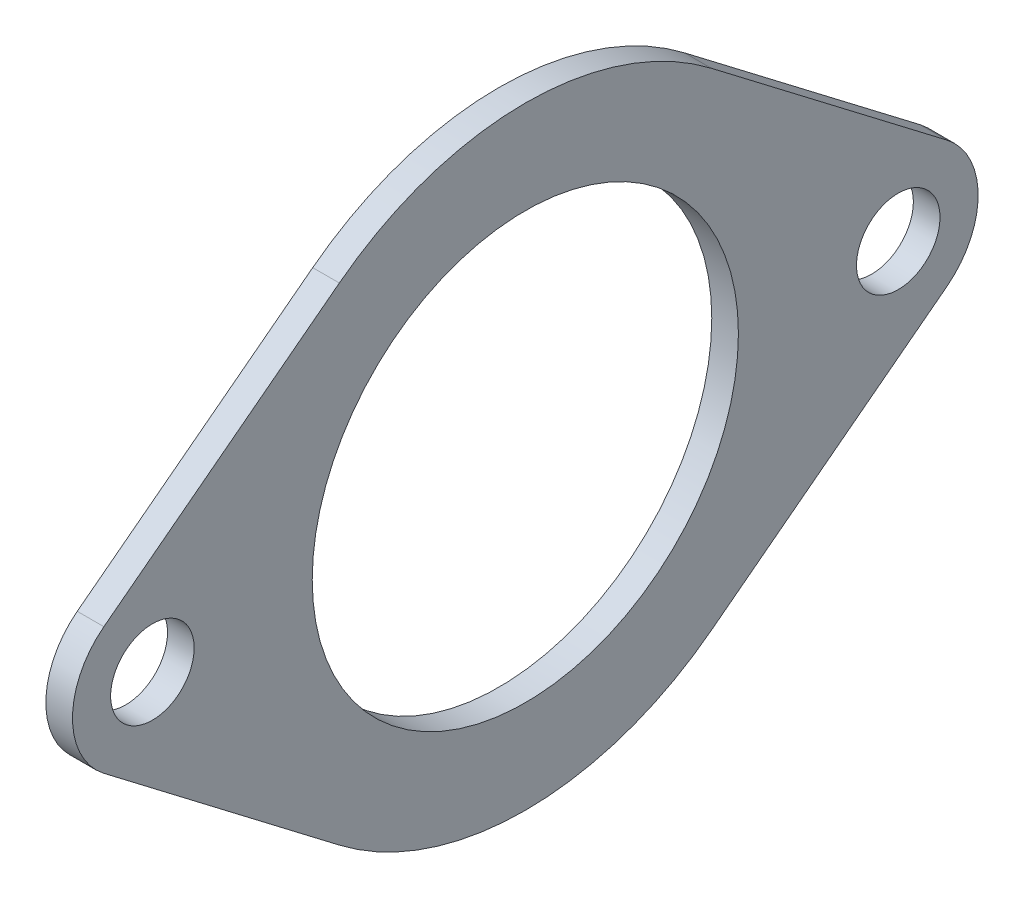
SolidWorks part; units mm, degrees
material "6061-T6 (SS)"
ref_plane "Front Plane" through (0, 0, 0) normal (0, 0, 1) x (1, 0, 0)
ref_plane "Top Plane" through (0, 0, 0) normal (0, 1, 0) x (1, 0, 0)
ref_plane "Right Plane" through (0, 0, 0) normal (1, 0, 0) x (0, 0, -1)
sketch "Sketch1" plane through (0, 0, 0) normal (1, 0, 0) x (0, 0, -1)
  line L0 (22.225, 0) -> (-22.225, 0) construction
  line L1 (-25.1165, -3.7842) -> (-11.0842, -14.5063)
  line L3 (-25.1165, 3.7842) -> (-11.0842, 14.5063)
  line L4 (25.1165, 3.7842) -> (11.0842, 14.5063)
  line L5 (25.1165, -3.7842) -> (11.0842, -14.5063)
  circle A0 centre (0, 0) radius 12.7
  arc A1 (-11.0842, -14.5063) -> (11.0842, -14.5063) centre (0, 0) ccw
  circle A2 centre (22.225, 0) radius 2.4892
  circle A3 centre (-22.225, 0) radius 2.4892
  arc A4 (25.1165, -3.7842) -> (25.1165, 3.7842) centre (22.225, 0) ccw
  arc A5 (-25.1165, 3.7842) -> (-25.1165, -3.7842) centre (-22.225, 0) ccw
  arc A6 (11.0842, 14.5063) -> (-11.0842, 14.5063) centre (0, 0) ccw
  point P7 (0, 0)
  dimension "D1" = 25.4
  dimension "D2" = 36.5125
  dimension "D4" = 4.9784
  dimension "D5" = 9.525
  dimension "D3" = 44.45
extrude "Boss-Extrude1" add sketch "Sketch1" along normal mid plane 1.5875
